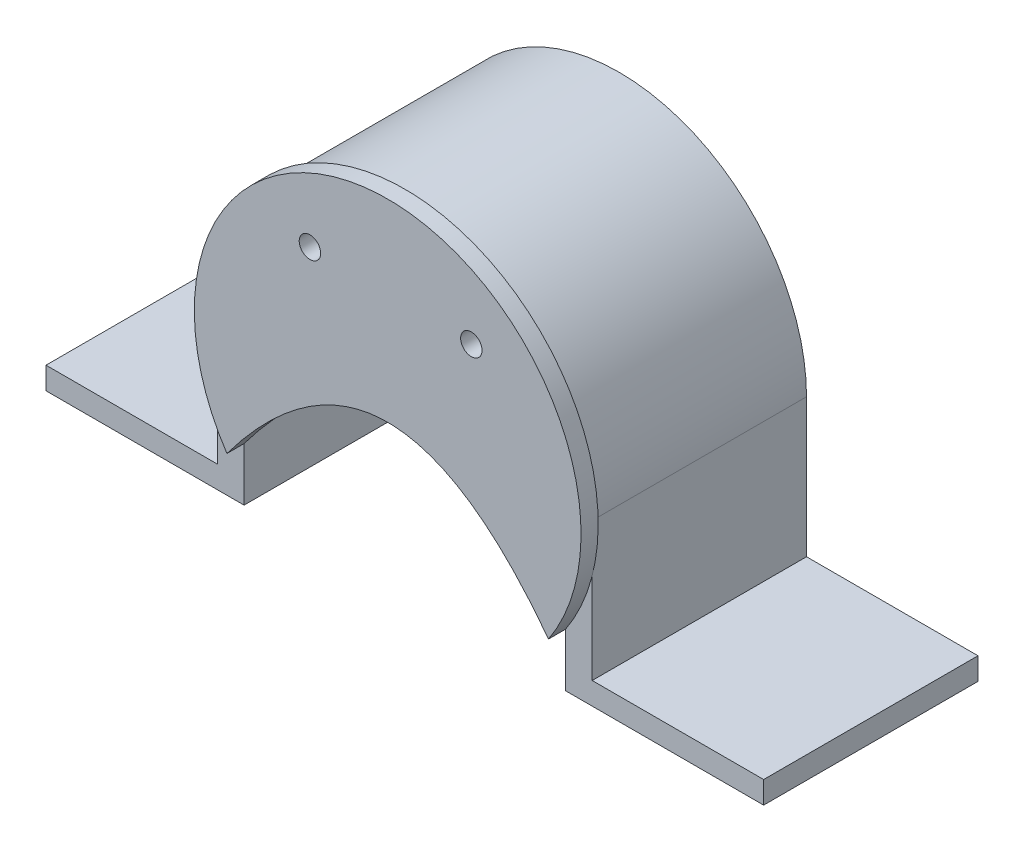
SolidWorks part; units mm, degrees
ref_plane "Front Plane" through (0, 0, 0) normal (0, 0, 1) x (1, 0, 0)
ref_plane "Top Plane" through (0, 0, 0) normal (0, 1, 0) x (1, 0, 0)
ref_plane "Right Plane" through (0, 0, 0) normal (1, 0, 0) x (0, 0, -1)
sketch "Sketch1" plane through (0, 0, 0) normal (0, 0, 1) x (1, 0, 0)
  line L0 (18.75, 0) -> (18.75, -18.75)
  line L1 (18.75, -18.75) -> (36.0004, -18.75)
  line L2 (-18.75, 0) -> (-18.75, -18.75)
  line L4 (21.851, -16.1604) -> (41.851, -16.1604)
  line L5 (41.851, -16.1604) -> (41.851, -18.75)
  line L6 (41.851, -18.75) -> (36.0004, -18.75)
  line L7 (21.851, -16.1604) -> (21.851, 0)
  line L8 (-21.851, 0) -> (-21.851, -16.1604)
  line L10 (-41.851, -16.1604) -> (-41.851, -18.75)
  line L13 (-21.851, -16.1604) -> (-41.851, -16.1604)
  line L14 (-18.75, -18.75) -> (-41.851, -18.75)
  arc A0 (18.75, 0) -> (-18.75, 0) centre (0, 0) ccw
  arc A1 (21.851, 0) -> (-21.851, 0) centre (0, 0) ccw
  point P4 (0, 18.75)
  dimension "D1" = 37.5
  dimension "D2" = 18.75
  dimension "D3" = 18.75
  dimension "D4" = 20
  dimension "D5" = 20
extrude "Boss-Extrude1" add sketch "Sketch1" along normal blind 25
ref_plane "Plane1" through (0, 0, 25) normal (0, 0, 1) x (1, 0, 0)
sketch "Sketch2" plane through (0, 0, 25) normal (0, 0, 1) x (1, 0, 0)
  line L0 (18.75, 0) -> (18.75, -18.75) construction
  line L1 (-18.75, 0) -> (-18.75, -18.75) construction
  arc A0 (18.75, -12.5308) -> (-18.75, -12.5308) centre (0, 0) ccw
  circle A2 centre (9.7564, 12.7517) radius 1.25
  circle A3 centre (-9.0669, 13.152) radius 1.25
  spline S0 degree 2 poles (-18.75, -12.5308) (0, 12.5308) (18.75, -12.5308) knots 0 0 0 1 1 1
  dimension "D2" = 2.5
  dimension "D3" = 2.5
extrude "Boss-Extrude2" add sketch "Sketch2" along normal blind 2 separate body
